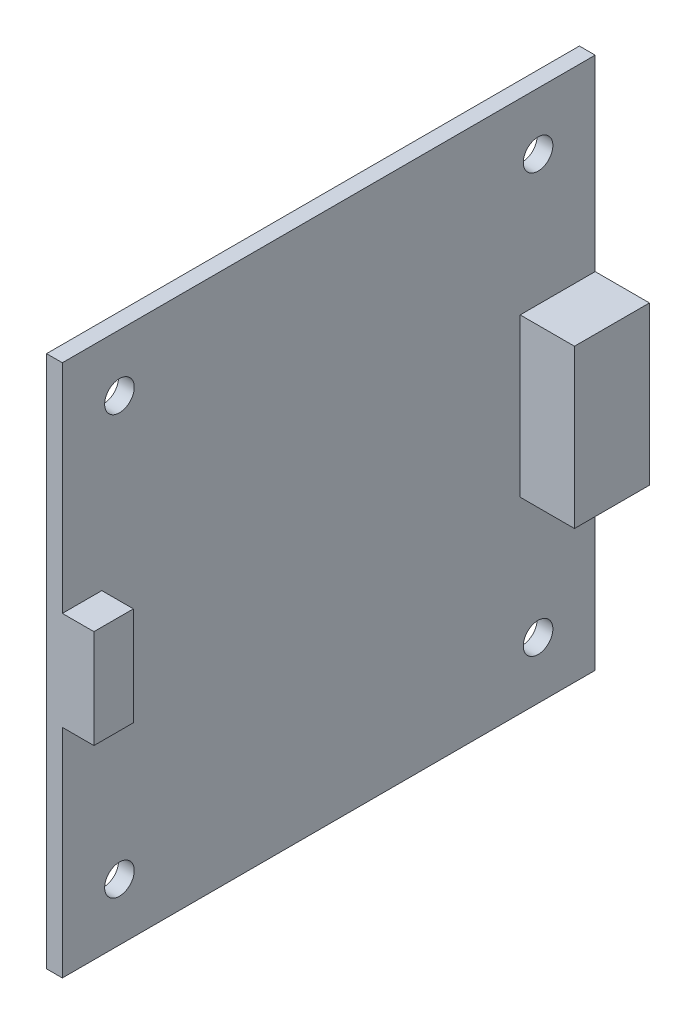
SolidWorks part; units mm, degrees
ref_plane "Front Plane" through (0, 0, 0) normal (1, 0, 0) x (0, 1, 0)
ref_plane "Top Plane" through (0, 0, 0) normal (0, 0, 1) x (0, 1, 0)
ref_plane "Right Plane" through (0, 0, 0) normal (0, 1, 0) x (-1, 0, 0)
sketch "Sketch1" plane through (0, 0, 0) normal (1, 0, 0) x (0, 1, 0)
  line L1 (-27, 27) -> (27, 27)
  line L2 (-27, 27) -> (-27, -27)
  line L3 (-27, -27) -> (27, -27)
  line L4 (27, 27) -> (27, -27)
  line L5 (-27, 27) -> (27, -27) construction
  line L6 (-27, -27) -> (27, 27) construction
  point P0 (0, 0)
  dimension "D1" = 54
  dimension "D2" = 54
extrude "Boss-Extrude1" add sketch "Sketch1" along normal blind 1.6
sketch "Sketch2" plane through (1.6, 0, 0) normal (1, 0, 0) x (0, 1, 0)
  line L0 (-21.2132, 21.2132) -> (21.2132, -21.2132) construction
  line L1 (-21.2132, -21.2132) -> (21.2132, 21.2132) construction
  line L2 (-21.2132, 21.2132) -> (-21.2132, -21.2132) construction
  line L3 (-21.2132, -21.2132) -> (21.2132, -21.2132) construction
  circle A0 centre (-21.2132, 21.2132) radius 1.5
  circle A1 centre (21.2132, 21.2132) radius 1.5
  circle A2 centre (-21.2132, -21.2132) radius 1.5
  circle A3 centre (21.2132, -21.2132) radius 1.5
  point P8 (0, 0)
  point P9 (0, 0)
  point P10 (-23.0177, -17.8993)
  point P11 (0, 0)
  dimension "D1" = 3
  dimension "D2" = 60
  dimension "D3" = 60
extrude "Cut-Extrude1" cut sketch "Sketch2" against normal through all
sketch "Sketch3" plane through (0, 0, 0) normal (-1, 0, 0) x (0, -1, 0)
  line L1 (-2.1, 1.6) -> (2.1, 1.6)
  line L2 (-2.1, 1.6) -> (-2.1, -1.6)
  line L3 (-2.1, -1.6) -> (2.1, -1.6)
  line L4 (2.1, 1.6) -> (2.1, -1.6)
  line L5 (-2.1, 1.6) -> (2.1, -1.6) construction
  line L6 (-2.1, -1.6) -> (2.1, 1.6) construction
  point P0 (0, 0)
  dimension "D1" = 4.2
  dimension "D2" = 3.2
extrude "Boss-Extrude2" add sketch "Sketch3" along normal blind 1.2
sketch "Sketch4" plane through (1.6, 0, 0) normal (1, 0, 0) x (0, 1, 0)
  line L5 (-27, -27) -> (27, -27) construction
  line L6 (-8, -27) -> (8, -27)
  line L7 (-8, -27) -> (-8, -19.4)
  line L8 (-8, -19.4) -> (8, -19.4)
  line L9 (8, -27) -> (8, -19.4)
  point P12 (0, -27)
  point P13 (0, -19.4)
  dimension "D1" = 16
  dimension "D2" = 7.6
extrude "Boss-Extrude3" add sketch "Sketch4" along normal blind 5.5
sketch "Sketch5" plane through (1.6, 0, 0) normal (1, 0, 0) x (0, 1, 0)
  line L0 (27, 27) -> (-27, 27) construction
  line L1 (-5, 27) -> (5, 27)
  line L2 (-5, 27) -> (-5, 23)
  line L3 (-5, 23) -> (5, 23)
  line L4 (5, 27) -> (5, 23)
  point P6 (0, 27)
  point P7 (0, 23)
  dimension "D1" = 10
  dimension "D2" = 4
extrude "Boss-Extrude4" add sketch "Sketch5" along normal blind 3.2
